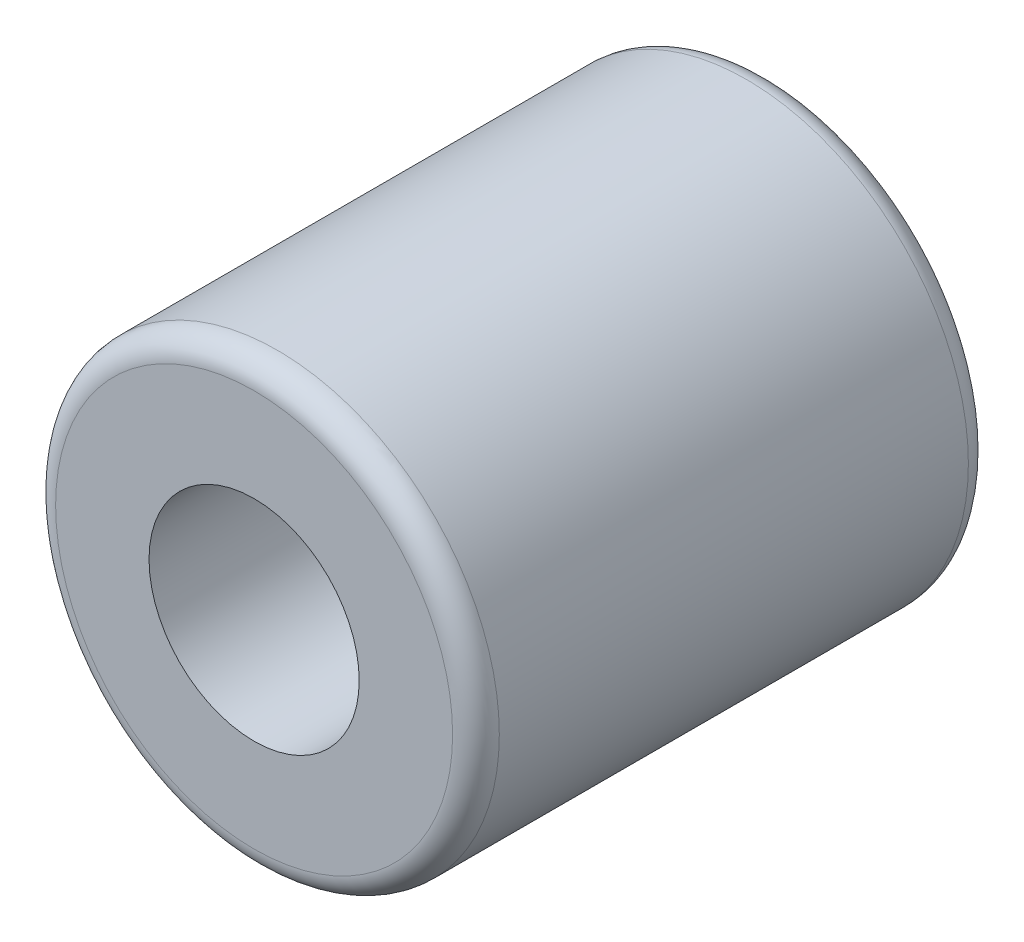
SolidWorks part; units mm, degrees
material "ABS"
ref_plane "Front Plane" through (0, 0, 0) normal (0, 0, 1) x (1, 0, 0)
ref_plane "Top Plane" through (0, 0, 0) normal (0, 1, 0) x (1, 0, 0)
ref_plane "Right Plane" through (0, 0, 0) normal (1, 0, 0) x (0, 0, -1)
sketch "Sketch2" plane through (0, 0, 42.805) normal (0, 0, 1) x (1, 0, 0)
  circle A0 centre (-51.25, 23.184) radius 4.75
  arc A1 (-47.75, 23.184) -> (-49.5, 26.2151) centre (-51.25, 23.184) ccw construction
  circle A2 centre (-51.25, 23.184) radius 2.25
  dimension "D1" = 4.5
  dimension "D2" = 2.5
extrude "Boss-Extrude1" add sketch "Sketch2" along normal up to surface (11.0432 mm away)
fillet "Fillet1" radius 0.5 2 edges at (-46.5, 23.184, 53.8482) (-46.5, 23.184, 42.805)
